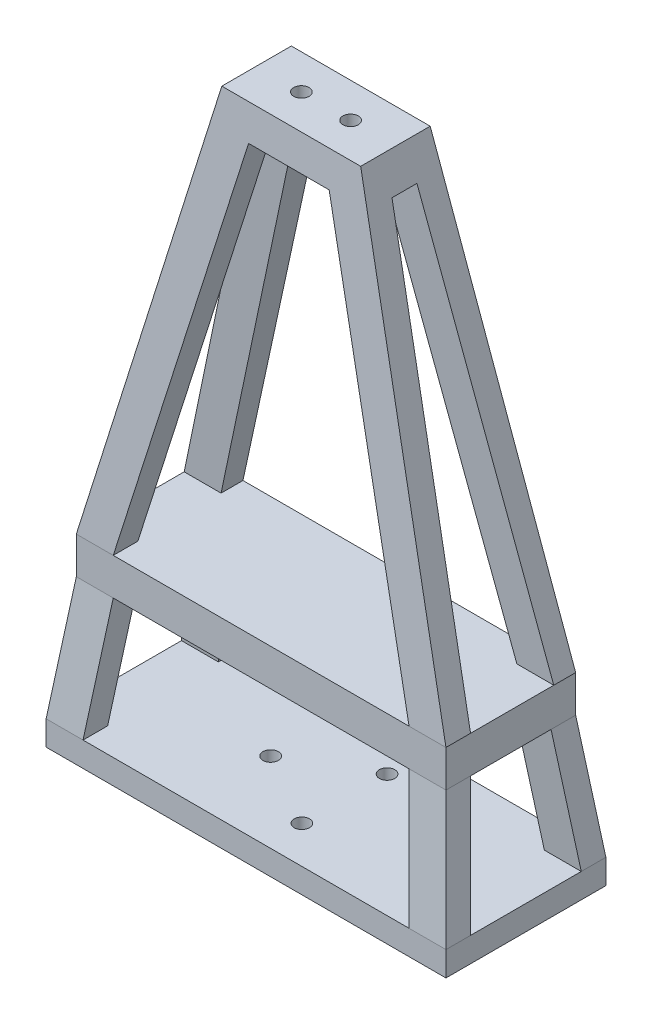
SolidWorks part; units mm, degrees
ref_plane "Front Plane" through (0, 0, 0) normal (0, 0, 1) x (1, 0, 0)
ref_plane "Top Plane" through (0, 0, 0) normal (0, 1, 0) x (1, 0, 0)
ref_plane "Right Plane" through (0, 0, 0) normal (1, 0, 0) x (0, 0, -1)
sketch "Sketch1" plane through (0, 0, 0) normal (0, 1, 0) x (1, 0, 0)
  line L1 (0, 0) -> (65, 0)
  line L2 (0, 0) -> (0, 26)
  line L3 (0, 26) -> (65, 26)
  line L4 (65, 0) -> (65, 26)
  dimension "D1" = 65
  dimension "D2" = 26
extrude "Boss-Extrude1" add sketch "Sketch1" along normal blind 4
sketch "Sketch2" plane through (0, 4, 0) normal (0, 1, 0) x (1, 0, 0)
  line L0 (0, 26) -> (0, 0) construction
  line L2 (65, 26) -> (0, 26) construction
  line L3 (23.5, 13) -> (35.5, 19.9282) construction
  line L4 (35.5, 19.9282) -> (35.5, 6.0718) construction
  line L5 (35.5, 6.0718) -> (23.5, 13) construction
  circle A0 centre (31.5, 13) radius 8 construction
  circle A1 centre (23.5, 13) radius 1.25
  circle A2 centre (35.5, 19.9282) radius 1.25
  circle A3 centre (35.5, 6.0718) radius 1.25
  dimension "D1" = 16
  dimension "D4" = 2.5
  dimension "D2" = 31.5
  dimension "D3" = 13
hole_wizard "Ø2.5mm Dowel Hole1" positions "3DSketch1" profile "Sketch4" hole size "Ø2.5" standard "ANSI Metric"
sketch3d "3DSketch1"
  point P0 (23.5, 4, -13)
  point P3 (35.5, 4, -19.9282)
  point P6 (35.5, 4, -6.0718)
sketch "Sketch4" plane through (23.5, 4, -13) normal (1, 0, 0) x (0, 0, 1)
  line L0 (0, 0) -> (0, 5.7511)
  line L1 (0, 5.7511) -> (1.25, 5)
  line L2 (1.25, 5) -> (1.25, 0)
  line L5 (1.25, 0) -> (0, 0)
  line L10 (0, 5.7511) -> (-1.25, 5) construction
  line L11 (0, -6.35) -> (0, 107.95) construction
  dimension "Hole Dia." = 2.5
  dimension "Hole Depth" = 5
  dimension "Drill Angle" = 118
sketch "Sketch6" plane through (0, 4, 0) normal (0, 1, 0) x (1, 0, 0)
  line L1 (0, 26) -> (65, 26)
  line L2 (0, 26) -> (0, 0)
  line L3 (0, 0) -> (65, 0)
  line L4 (65, 26) -> (65, 0)
extrude "Boss-Extrude2" add sketch "Sketch6" along normal blind 20 draft 7
sketch "Sketch7" plane through (0, 24, 0) normal (0, 1, 0) x (1, 0, 0)
  line L0 (2.4557, 23.5443) -> (2.4557, 2.4557) construction
  line L1 (8.4557, 19.5443) -> (56.5443, 19.5443)
  line L2 (8.4557, 19.5443) -> (8.4557, 6.4557)
  line L3 (8.4557, 6.4557) -> (56.5443, 6.4557)
  line L4 (56.5443, 19.5443) -> (56.5443, 6.4557)
  line L5 (62.5443, 2.4557) -> (62.5443, 23.5443) construction
  line L6 (62.5443, 23.5443) -> (2.4557, 23.5443) construction
  line L7 (2.4557, 2.4557) -> (62.5443, 2.4557) construction
  dimension "D1" = 6
  dimension "D2" = 6
  dimension "D3" = 4
  dimension "D4" = 4
extrude "Cut-Extrude1" cut sketch "Sketch7" against normal blind 20 draft 7 draft outward yes
sketch "Sketch9" plane through (0, 0, -26) normal (0, 0, -1) x (-1, 0, 0)
  line L0 (-59, 4) -> (-6, 4)
  line L1 (-65, 4) -> (0, 4) construction
  line L2 (-6, 4) -> (-8.4557, 24)
  line L3 (-62.5443, 24) -> (-2.4557, 24) construction
  line L4 (-8.4557, 24) -> (-56.5443, 24)
  line L5 (-56.5443, 24) -> (-59, 4)
  dimension "D1" = 83
  dimension "D2" = 83
  dimension "D3" = 6
  dimension "D4" = 6
extrude "Cut-Extrude3" cut sketch "Sketch9" against normal blind 33
sketch "Sketch10" plane through (65, 0, 0) normal (1, 0, 0) x (0, 0, -1)
  line L0 (4, 4) -> (22, 4)
  line L1 (0, 4) -> (26, 4) construction
  line L2 (22, 4) -> (19.5443, 24)
  line L3 (2.4557, 24) -> (23.5443, 24) construction
  line L4 (19.5443, 24) -> (6.4557, 24)
  line L5 (6.4557, 24) -> (4, 4)
  dimension "D1" = 83
  dimension "D2" = 83
  dimension "D3" = 4
  dimension "D4" = 4
extrude "Cut-Extrude4" cut sketch "Sketch10" against normal blind 70
sketch "Sketch11" plane through (0, 24, 0) normal (0, 1, 0) x (1, 0, 0)
  line L1 (2.4557, 23.5443) -> (62.5443, 23.5443)
  line L2 (2.4557, 23.5443) -> (2.4557, 2.4557)
  line L3 (2.4557, 2.4557) -> (62.5443, 2.4557)
  line L4 (62.5443, 23.5443) -> (62.5443, 2.4557)
extrude "Boss-Extrude3" add sketch "Sketch11" along normal blind 6
sketch "Sketch12" plane through (0, 30, 0) normal (0, 1, 0) x (1, 0, 0)
  line L1 (2.4557, 23.5443) -> (62.5443, 23.5443)
  line L2 (2.4557, 23.5443) -> (2.4557, 2.4557)
  line L3 (2.4557, 2.4557) -> (62.5443, 2.4557)
  line L4 (62.5443, 23.5443) -> (62.5443, 2.4557)
extrude "Boss-Extrude5" add sketch "Sketch12" along normal blind 70 draft 4
sketch "Sketch13" plane through (0, 0, -23.5443) normal (0, 0, -1) x (-1, 0, 0)
  line L0 (-62.5443, 30) -> (-43.7879, 100)
  line L1 (-57.6494, 100) -> (-7.3506, 100) construction
  line L2 (-2.4557, 30) -> (-21.2121, 100)
  line L3 (-62.5443, 30) -> (-2.4557, 30) construction
  line L4 (-39.0499, 94.5) -> (-25.9501, 94.5)
  line L5 (-25.9501, 94.5) -> (-8.4557, 30)
  line L6 (-8.4557, 30) -> (-56.5443, 30)
  line L7 (-56.5443, 30) -> (-39.0499, 94.5)
  line L12 (-62.5443, 30) -> (-62.5443, 100)
  line L13 (-62.5443, 100) -> (-43.7879, 100)
  line L14 (-21.2121, 100) -> (-2.4557, 100)
  line L15 (-2.4557, 100) -> (-2.4557, 30)
  dimension "D1" = 75
  dimension "D2" = 75
  dimension "D3" = 6
  dimension "D4" = 6
  dimension "D5" = 5.5
  dimension "D6" = 6
  dimension "D7" = 6
extrude "Cut-Extrude5" cut sketch "Sketch13" against normal blind 55
sketch "Sketch14" plane through (62.5443, 0, 0) normal (1, 0, 0) x (0, 0, -1)
  line L0 (6.4557, 30) -> (19.9866, 30)
  line L1 (2.4557, 30) -> (23.5443, 30) construction
  line L6 (18.6494, 100) -> (23.5443, 30) construction
  line L9 (6.4557, 30) -> (10.966, 94.5)
  line L11 (18.6494, 100) -> (7.3506, 100) construction
  line L12 (10.966, 94.5) -> (15.0243, 94.5)
  line L13 (15.0243, 94.5) -> (19.9866, 30)
  dimension "D1" = 4
  dimension "D2" = 3.5577
  dimension "D3" = 5.5
  dimension "D5" = 4
extrude "Cut-Extrude6" cut sketch "Sketch14" against normal blind 67
sketch "Sketch15" plane through (0, 100, 0) normal (0, 1, 0) x (1, 0, 0)
  line L0 (21.2121, 13) -> (28.5, 13) construction
  line L3 (28.5, 7.3506) -> (28.5, 18.6494) construction
  line L4 (21.2121, 7.3506) -> (43.7879, 7.3506) construction
  line L5 (43.7879, 18.6494) -> (21.2121, 18.6494) construction
  line L6 (36.5, 7.3506) -> (36.5, 18.6494) construction
  line L7 (21.2121, 7.3506) -> (21.2121, 18.6494) construction
  line L8 (36.5, 13) -> (43.7879, 13) construction
  line L9 (43.7879, 18.6494) -> (43.7879, 7.3506) construction
  line L10 (28.5, 13) -> (36.5, 13) construction
  circle A0 centre (36.5, 13) radius 1.25
  circle A1 centre (28.5, 13) radius 1.25
  point P1 (28.5, 13)
  point P4 (36.5, 13)
  point P23 (36.5, 13)
  point P25 (28.5, 13)
  dimension "D2" = 2.5
  dimension "D1" = 8
hole_wizard "Ø2.5mm Dowel Hole2" positions "Sketch15" profile "Sketch16" hole size "Ø2.5" standard "ANSI Metric"
sketch "Sketch16" plane through (28.5, 100, -13) normal (1, 0, 0) x (0, 0, 1)
  line L0 (0, 0) -> (0, 5.7511)
  line L1 (0, 5.7511) -> (1.25, 5)
  line L2 (1.25, 5) -> (1.25, 0)
  line L5 (1.25, 0) -> (0, 0)
  line L10 (0, 5.7511) -> (-1.25, 5) construction
  line L11 (0, -6.35) -> (0, 107.95) construction
  dimension "Hole Dia." = 2.5
  dimension "Hole Depth" = 5
  dimension "Drill Angle" = 118
